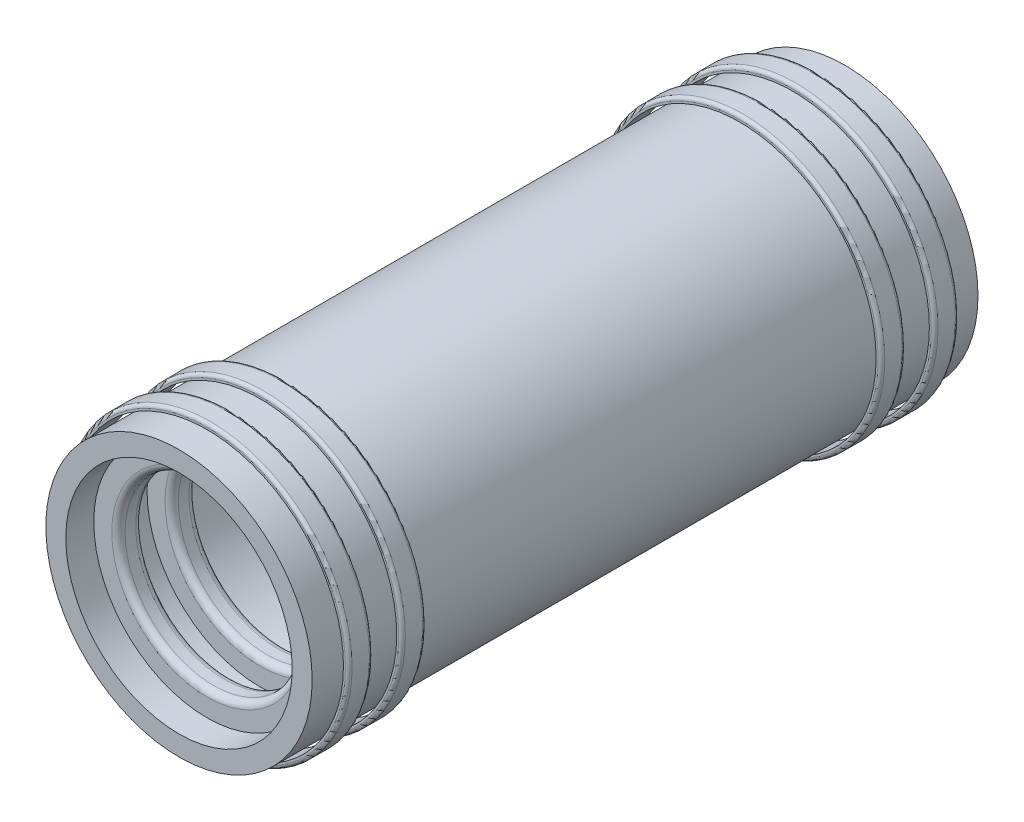
SolidWorks part; units mm, degrees
material "PET"
ref_plane "Front Plane" through (0, 0, 0) normal (0, 0, 1) x (1, 0, 0)
ref_plane "Top Plane" through (0, 0, 0) normal (0, 1, 0) x (1, 0, 0)
ref_plane "Right Plane" through (0, 0, 0) normal (1, 0, 0) x (0, 0, -1)
sketch "Sketch1" plane through (0, 0, 0) normal (0, 0, 1) x (1, 0, 0)
  circle A0 centre (0, 0) radius 20
  circle A1 centre (0, 0) radius 17
  dimension "D1" = 40
  dimension "D2" = 34
extrude "Boss-Extrude1" add sketch "Sketch1" along normal blind 100
sketch "Sketch2" plane through (0, 0, 0) normal (0, 1, 0) x (1, 0, 0)
  line L1 (20, -100) -> (20, 0) construction
  line L2 (20, 0) -> (-20, 0) construction
  line L3 (-20, -100) -> (20, -100) construction
  circle A0 centre (20, -7) radius 3
  circle A1 centre (20, -50) radius 3
  circle A2 centre (20, -93) radius 3
  dimension "D1" = 6
  dimension "D2" = 6
  dimension "D3" = 6
  dimension "D4" = 7
  dimension "D5" = 7
extrude "Boss-Extrude2" [suppressed] add sketch "Sketch2" along normal mid plane 100
mirror "Mirror1" [suppressed] about plane through (0, 0, 0) normal (1, 0, 0)
sketch "Sketch3" plane through (0, 0, 0) normal (0, 0, -1) x (-1, 0, 0)
  line L1 (-28.064, 5) -> (-19.3649, 5)
  line L2 (-28.064, 5) -> (-28.064, -5)
  line L3 (-28.064, -5) -> (-19.3649, -5)
  line L5 (19.3649, 5) -> (30.1764, 5)
  line L7 (19.3649, -5) -> (30.1764, -5)
  line L8 (30.1764, 5) -> (30.1764, -5)
  arc A0 (-19.3649, -5) -> (19.3649, -5) centre (0, 0) ccw
  circle A1 centre (0, 0) radius 67.5291
  arc A2 (19.3649, 5) -> (-19.3649, 5) centre (0, 0) ccw
  dimension "D3" = 20
  dimension "D1" = 10
  dimension "D2" = 5
  dimension "D4" = 10
extrude "Cut-Extrude1" [suppressed] cut sketch "Sketch3" against normal through all contours L1 A2 L5 L8 L7 A0 L3 L2
sketch "Sketch4" [suppressed] plane through (0, -5, 0) normal (0, -1, 0) x (1, 0, 0)
  circle A0 centre (-20, 93) radius 1.25
  circle A1 centre (-20, 50) radius 1.25
  circle A2 centre (-20, 7) radius 1.25
  dimension "D1" = 2.5
  dimension "D2" = 2.5
  dimension "D3" = 2.5
extrude "Cut-Extrude2" [suppressed] cut sketch "Sketch4" against normal mid plane 100
mirror "Mirror2" [suppressed] about plane through (0, 0, 0) normal (1, 0, 0)
sketch "Sketch5" [suppressed] plane through (0, -5, 0) normal (0, -1, 0) x (1, 0, 0)
  circle A0 centre (-20, 93) radius 3
  circle A1 centre (-20, 50) radius 3
  circle A2 centre (-20, 7) radius 3
  dimension "D1" = 6
  dimension "D2" = 6
  dimension "D3" = 6
extrude "Cut-Extrude3" [suppressed] cut sketch "Sketch5" along normal through all contours A0
mirror "Mirror3" [suppressed] about plane through (0, 0, 0) normal (0, 1, 0)
mirror "Mirror4" [suppressed] about plane through (0, 0, 0) normal (1, 0, 0)
fillet "Fillet1" [suppressed] radius 5
sketch "Sketch7" plane through (0, 0, 0) normal (0, 1, 0) x (1, 0, 0)
  line L0 (-20, -100) -> (20, -100) construction
  line L1 (-21.5, -92) -> (-13.1, -92) construction
  line L2 (-21.5, -92) -> (-21.5, -96) construction
  line L3 (-21.5, -96) -> (-13.1, -96) construction
  line L4 (-13.1, -92) -> (-13.1, -96) construction
  line L5 (-21.5, -88) -> (-13.1, -88) construction
  line L6 (-21.5, -88) -> (-21.5, -84) construction
  line L7 (-21.5, -84) -> (-13.1, -84) construction
  line L8 (-13.1, -88) -> (-13.1, -84) construction
  line L9 (0, -100) -> (0, 0) construction
  line L10 (-17, -100) -> (17, -100) construction
  line L11 (-17, -100) -> (-17, -81.9282) construction
  line L12 (-13.3, -87.8) -> (-13.3, -84.2)
  line L13 (-21.3, -84.2) -> (-13.3, -84.2)
  line L14 (-21.3, -87.8) -> (-21.3, -84.2)
  line L15 (-21.3, -87.8) -> (-13.3, -87.8)
  line L16 (-21.3, -92.2) -> (-13.3, -92.2)
  line L17 (-13.3, -92.2) -> (-13.3, -95.8)
  line L18 (-21.3, -95.8) -> (-13.3, -95.8)
  line L19 (-21.3, -92.2) -> (-21.3, -95.8)
  line L20 (-20, 0) -> (-20, -100) construction
  dimension "D1" = 4
  dimension "D2" = 4
  dimension "D3" = 17
  dimension "D4" = 3.9
  dimension "D5" = 4
  dimension "D6" = 4
  dimension "D9" = 1.5
  dimension "D7" = 0.2
  dimension "D8" = 0.2
revolve "Revolve1" add sketch "Sketch7" angle 360 about L9
fillet "Fillet2" radius 1 4 edges at (13.3, 0, 95.8) (13.3, 0, 92.2) (13.3, 0, 87.8) (13.3, 0, 84.2)
ref_plane "Plane1" through (0, 0, 50) normal (0, 0, -1) x (-1, 0, 0)
mirror "Mirror5" about plane through (0, 0, 50) normal (0, 0, -1) of "Fillet2", "Revolve1"
sketch "Sketch8" plane through (0, 0, 0) normal (0, 1, 0) x (1, 0, 0)
  line L1 (-31.5459, 10.0739) -> (31.1344, 10.0739)
  line L2 (-31.5459, 10.0739) -> (-31.5459, -108.5631)
  line L3 (-31.5459, -108.5631) -> (31.1344, -108.5631)
  line L4 (31.1344, 10.0739) -> (31.1344, -108.5631)
fillet "Fillet3" radius 0.5 8 edges at (21.3, 0, 7.8) (21.3, 0, 4.2) (21.3, 0, 15.8) (21.3, 0, 12.2) (21.3, 0, 95.8) (21.3, 0, 92.2) (21.3, 0, 87.8) (21.3, 0, 84.2)
sketch "Sketch9" plane through (0, 0, 0) normal (0, 0, -1) x (-1, 0, 0)
  circle A0 centre (0, 0) radius 20
  circle A1 centre (0, 0) radius 20.5
  dimension "D1" = 40
  dimension "D2" = 0.5
extrude "Cut-Extrude4" cut sketch "Sketch9" against normal through all
